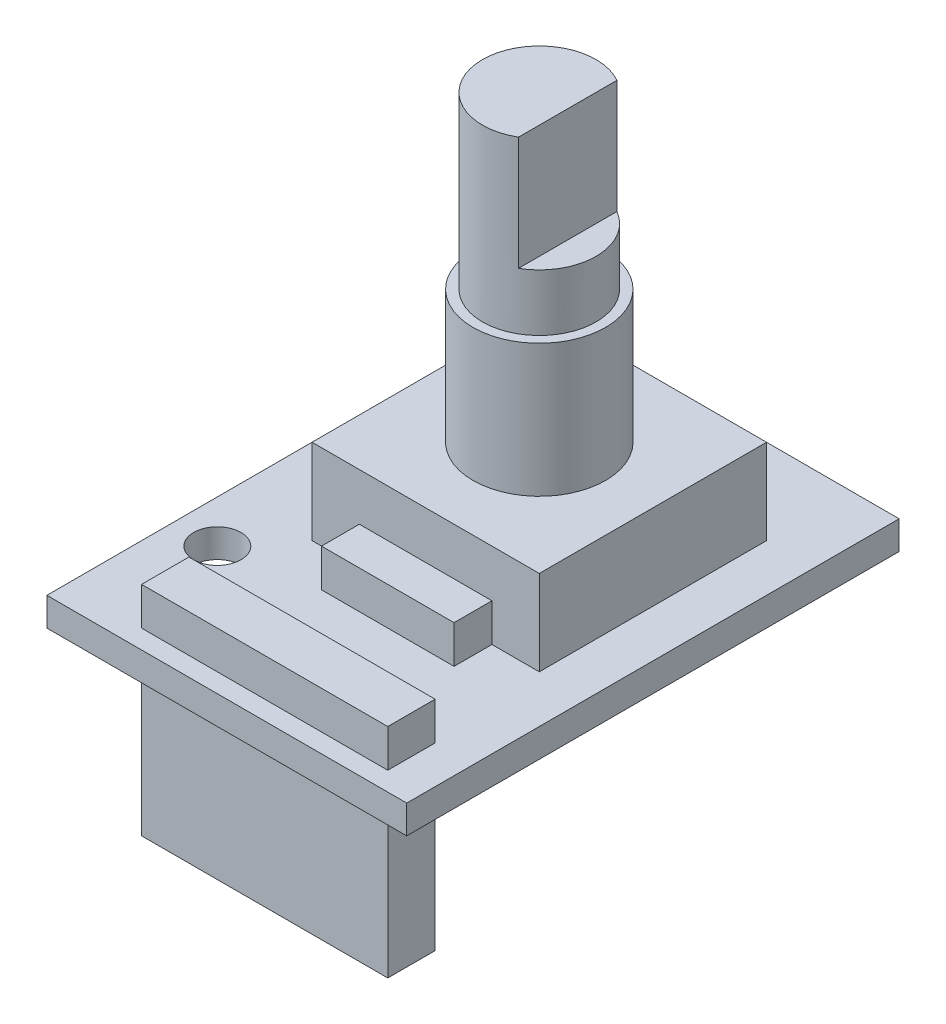
SolidWorks part; units mm, degrees
ref_plane "Piano frontale" through (0, 0, 0) normal (0, 0, 1) x (1, 0, 0)
ref_plane "Piano superiore" through (0, 0, 0) normal (0, 1, 0) x (1, 0, 0)
ref_plane "Piano destro" through (0, 0, 0) normal (1, 0, 0) x (0, 0, -1)
sketch "Schizzo1" plane through (0, 0, 0) normal (0, 1, 0) x (1, 0, 0)
  line L1 (-9.5, -13) -> (9.5, -13)
  line L2 (-9.5, -13) -> (-9.5, 13)
  line L3 (-9.5, 13) -> (9.5, 13)
  line L4 (9.5, -13) -> (9.5, 13)
  dimension "D1" = 19
  dimension "D2" = 26
  dimension "D3" = 13
  dimension "D4" = 9.5
extrude "Estrusione-Estrusione1" add sketch "Schizzo1" along normal blind 1.5
sketch "Schizzo2" plane through (0, 1.5, 0) normal (0, 1, 0) x (1, 0, 0)
  line L0 (9.5, -13) -> (9.5, 13) construction
  line L1 (-5, -3.5) -> (7, -3.5)
  line L2 (-5, -3.5) -> (-5, 8.5)
  line L3 (-5, 8.5) -> (7, 8.5)
  line L4 (7, -3.5) -> (7, 8.5)
  line L5 (9.5, 13) -> (-9.5, 13) construction
  dimension "D1" = 12
  dimension "D2" = 12
  dimension "D3" = 2.5
  dimension "D4" = 4.5
extrude "Estrusione-Estrusione2" add sketch "Schizzo2" along normal blind 4.5
sketch "Schizzo4" plane through (0, 6, 0) normal (0, 1, 0) x (1, 0, 0)
  line L1 (7, 8.5) -> (-5, 8.5) construction
  line L3 (7, -3.5) -> (7, 8.5) construction
  circle A0 centre (1, 2.5) radius 3.5
  dimension "D2" = 6
  dimension "D3" = 7
  dimension "D1" = 6
extrude "Estrusione-Estrusione3" add sketch "Schizzo4" along normal blind 7
sketch "Schizzo5" plane through (0, 13, 0) normal (0, 1, 0) x (1, 0, 0)
  circle A0 centre (1, 2.5) radius 3
  circle A1 centre (1, 2.5) radius 3.5 construction
  dimension "D1" = 6
extrude "Estrusione-Estrusione4" add sketch "Schizzo5" along normal blind 9
sketch "Schizzo6" plane through (0, 22, 0) normal (0, 1, 0) x (1, 0, 0)
  line L0 (2.5, 5.0981) -> (2.5, -0.0981)
  circle A0 centre (1, 2.5) radius 3
  circle M3 centre (1, 2.5) radius 3
  dimension "D1" = 6
  dimension "D2" = 1.5
extrude "Taglio-Estrusione1" cut sketch "Schizzo6" against normal blind 6 contours L0 M3
sketch "Schizzo7" plane through (0, 1.5, 0) normal (0, 1, 0) x (1, 0, 0)
  line L0 (-9.5, 13) -> (-9.5, -13) construction
  line L1 (9.5, 13) -> (-9.5, 13) construction
  line L2 (-9.5, -13) -> (9.5, -13) construction
  circle A0 centre (-7.25, 7.75) radius 1.25
  circle A1 centre (-7.25, -6.25) radius 1.25
  dimension "D1" = 2.5
  dimension "D2" = 2.5
  dimension "D3" = 2.25
  dimension "D4" = 2.25
  dimension "D5" = 5.25
  dimension "D6" = 6.75
extrude "Taglio-Estrusione2" cut sketch "Schizzo7" against normal blind 6
sketch "Schizzo8" plane through (0, 1.5, 0) normal (0, 1, 0) x (1, 0, 0)
  line L0 (9.5, -13) -> (9.5, 13) construction
  line L1 (-5.5, -12) -> (7.5, -12)
  line L2 (-5.5, -12) -> (-5.5, -9.5)
  line L3 (-5.5, -9.5) -> (7.5, -9.5)
  line L4 (7.5, -12) -> (7.5, -9.5)
  line L5 (-9.5, -13) -> (9.5, -13) construction
  dimension "D1" = 2.5
  dimension "D2" = 13
  dimension "D3" = 2
  dimension "D4" = 1
extrude "Estrusione-Estrusione5" add sketch "Schizzo8" along normal blind 2 and the other way blind 9.5
sketch "Schizzo9" plane through (0, 0, 0) normal (0, -1, 0) x (1, 0, 0)
  line L1 (-2.75, 6.5) -> (6.5, 6.5)
  line L2 (-2.75, 6.5) -> (-2.75, -12)
  line L3 (-2.75, -12) -> (6.5, -12)
  line L4 (6.5, 6.5) -> (6.5, -12)
  line L5 (9.5, 13) -> (9.5, -13) construction
  line L6 (9.5, -13) -> (-9.5, -13) construction
  line L7 (-5.5, 9.5) -> (7.5, 9.5) construction
  circle A0 centre (-7.25, 6.25) radius 1.25 construction
  dimension "D1" = 4.5
  dimension "D2" = 3
  dimension "D3" = 1
  dimension "D4" = 3
extrude "Estrusione-Estrusione6" add sketch "Schizzo9" along normal blind 1.5
sketch "Schizzo10" plane through (0, 1.5, 0) normal (0, 1, 0) x (1, 0, 0)
  line L0 (7, 8.5) -> (-5, 8.5) construction
  line L1 (-2.5, 8.5) -> (4.5, 8.5)
  line L2 (-2.5, 8.5) -> (-2.5, 10.5)
  line L3 (-2.5, 10.5) -> (4.5, 10.5)
  line L4 (4.5, 8.5) -> (4.5, 10.5)
  line L5 (-5, -3.5) -> (7, -3.5) construction
  line L6 (-2.5, -3.5) -> (4.5, -3.5)
  line L7 (-2.5, -3.5) -> (-2.5, -5.5)
  line L8 (-2.5, -5.5) -> (4.5, -5.5)
  line L9 (4.5, -3.5) -> (4.5, -5.5)
  line L10 (-5, 8.5) -> (-5, -3.5) construction
  dimension "D1" = 7
  dimension "D2" = 2
  dimension "D3" = 2
  dimension "D4" = 7
  dimension "D5" = 2.5
  dimension "D6" = 2.5
extrude "Estrusione-Estrusione7" add sketch "Schizzo10" along normal blind 2
